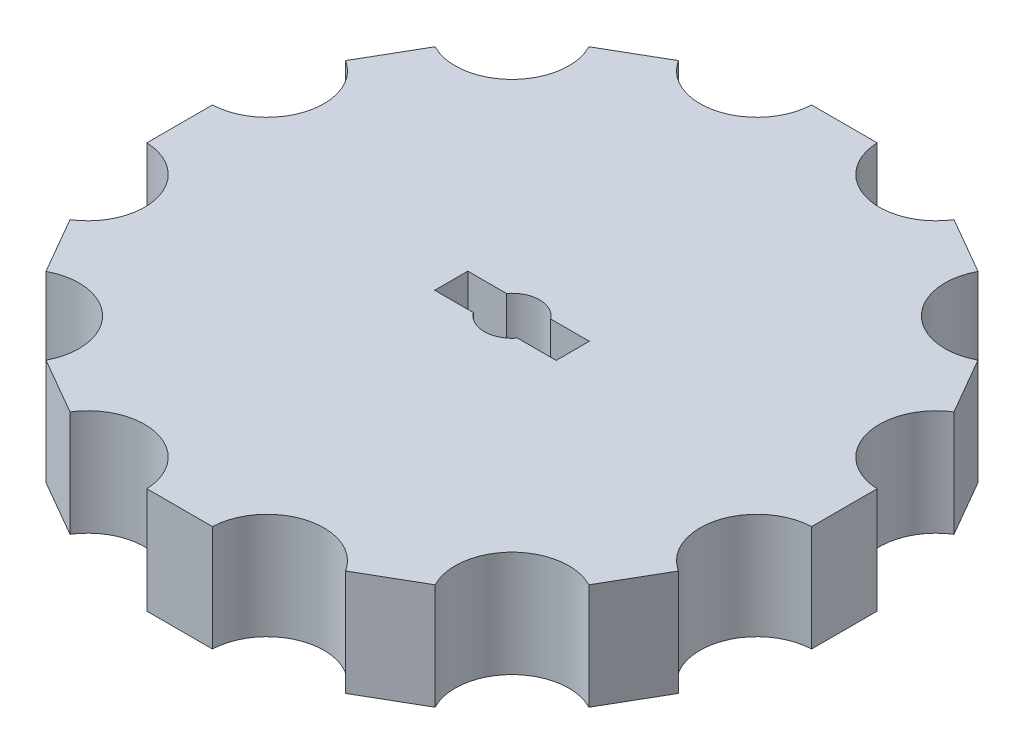
SolidWorks part; units mm, degrees
ref_plane "Front Plane" through (0, 0, 0) normal (0, 0, 1) x (1, 0, 0)
ref_plane "Top Plane" through (0, 0, 0) normal (0, 1, 0) x (1, 0, 0)
ref_plane "Right Plane" through (0, 0, 0) normal (1, 0, 0) x (0, 0, -1)
sketch "Sketch1" plane through (0, 0, 0) normal (0, 1, 0) x (1, 0, 0)
  line L0 (8.115, 30.2856) -> (3.165, 30.2856) construction
  line L1 (-8.115, -30.2856) -> (8.115, -30.2856)
  line L2 (8.115, -30.2856) -> (22.1706, -22.1706)
  line L3 (22.1706, -22.1706) -> (26.2281, -15.1428)
  line L4 (30.2856, -2.965) -> (30.2856, 0) construction
  line L5 (30.2856, 8.115) -> (27.7106, 12.575) construction
  line L6 (17.7106, 24.7456) -> (15.1428, 26.2281) construction
  line L7 (3.165, 30.2856) -> (-3.165, 30.2856) construction
  line L8 (-12.575, 27.7106) -> (-22.1706, 22.1706)
  line L9 (-22.1706, 22.1706) -> (-30.2856, 8.115)
  line L10 (-30.2856, 8.115) -> (-30.2856, -8.115)
  line L11 (-30.2856, -8.115) -> (-22.1706, -22.1706)
  line L12 (-22.1706, -22.1706) -> (-8.115, -30.2856)
  line L13 (12.4018, 27.8106) -> (8.115, 30.2856) construction
  line L14 (-8.115, 30.2856) -> (-12.4018, 27.8106) construction
  line L15 (-3.165, 30.2856) -> (-8.115, 30.2856) construction
  line L16 (2.9689, 30.0856) -> (-2.9689, 30.0856)
  line L17 (-12.4018, 27.8106) -> (-12.575, 27.7106) construction
  line L18 (17.6139, 24.5704) -> (12.4717, 27.5393)
  line L19 (27.5393, 12.4717) -> (24.5704, 17.6139)
  line L20 (30.0856, -2.9689) -> (30.0856, 2.9689)
  line L21 (24.4724, -17.7838) -> (27.5393, -12.4717)
  line L22 (12.3018, -27.6374) -> (17.6139, -24.5704)
  line L23 (-3.165, -30.0856) -> (2.9689, -30.0856)
  line L24 (-17.7838, -24.4724) -> (-12.4717, -27.5393)
  line L25 (-27.6374, -12.3018) -> (-24.5704, -17.6139)
  line L26 (-30.0856, 3.165) -> (-30.0856, -2.9689)
  line L27 (-24.4724, 17.7838) -> (-27.5393, 12.4717)
  line L28 (-12.4717, 27.5393) -> (-17.6139, 24.5704)
  line L29 (-12.3018, 27.6374) -> (-12.4717, 27.5393) construction
  line L30 (15.1428, 26.2281) -> (12.4018, 27.8106) construction
  line L31 (3.165, 30.0856) -> (2.9689, 30.0856) construction
  line L32 (3.165, 30.0856) -> (-2.9689, 30.0856) construction
  line L33 (22.1706, 22.1706) -> (17.7106, 24.7456) construction
  line L34 (17.7838, 24.4724) -> (17.6139, 24.5704) construction
  line L35 (26.2281, 15.1428) -> (22.1706, 22.1706) construction
  line L36 (27.6374, 12.3018) -> (27.5393, 12.4717) construction
  line L37 (27.7106, 12.575) -> (26.2281, 15.1428) construction
  line L38 (30.2856, 0) -> (30.2856, 8.115) construction
  line L39 (30.2856, -8.115) -> (30.2856, -2.965) construction
  line L40 (26.2281, -15.1428) -> (30.2856, -8.115) construction
  line L41 (30.0856, -3.165) -> (30.0856, -2.9689) construction
  circle A0 centre (0, 0) radius 30.2856 construction
  arc A1 (-12.4018, 27.8106) -> (-3.165, 30.2856) centre (-8.115, 30.2856) ccw construction
  arc A2 (3.165, 30.2856) -> (3.1678, 30.1195) centre (8.115, 30.2856) ccw construction
  arc A3 (-3.165, 30.2856) -> (-12.4018, 27.8106) centre (-8.115, 30.2856) ccw construction
  arc A4 (12.4018, 27.8106) -> (3.165, 30.2856) centre (8.115, 30.2856) ccw construction
  arc A5 (-12.4717, 27.5393) -> (-2.9689, 30.0856) centre (-8.115, 30.2856) ccw
  arc A6 (2.9689, 30.0856) -> (12.4717, 27.5393) centre (8.115, 30.2856) ccw
  arc A7 (17.6395, 24.6184) -> (24.5704, 17.6139) centre (22.1706, 22.1706) ccw
  arc A8 (27.5855, 12.5004) -> (30.0856, 2.9689) centre (30.2856, 8.115) ccw
  arc A9 (30.0856, -2.9689) -> (27.5393, -12.4717) centre (30.2856, -8.115) ccw
  arc A10 (24.7456, -17.7106) -> (17.6139, -24.5704) centre (22.1706, -22.1706) ccw
  arc A11 (12.575, -27.7106) -> (2.9689, -30.0856) centre (8.115, -30.2856) ccw
  arc A12 (-2.965, -30.2856) -> (-12.4717, -27.5393) centre (-8.115, -30.2856) ccw
  arc A13 (-17.7106, -24.7456) -> (-24.5704, -17.6139) centre (-22.1706, -22.1706) ccw
  arc A14 (-27.7106, -12.575) -> (-30.0856, -2.9689) centre (-30.2856, -8.115) ccw
  arc A15 (-30.2856, 2.965) -> (-27.5393, 12.4717) centre (-30.2856, 8.115) ccw
  arc A16 (-24.7456, 17.7106) -> (-17.6139, 24.5704) centre (-22.1706, 22.1706) ccw
  arc A17 (-12.5004, 27.5855) -> (-12.4717, 27.5393) centre (-8.115, 30.2856) ccw construction
  arc A18 (-12.575, 27.7106) -> (-12.5004, 27.5855) centre (-8.115, 30.2856) ccw construction
  arc A19 (-12.575, 27.7106) -> (-2.9689, 30.0856) centre (-8.115, 30.2856) ccw construction
  arc A20 (2.965, 30.2856) -> (2.9671, 30.1399) centre (8.115, 30.2856) ccw construction
  arc A21 (2.9671, 30.1399) -> (2.9689, 30.0856) centre (8.115, 30.2856) ccw construction
  arc A22 (12.3163, 27.6681) -> (12.4018, 27.8106) centre (8.115, 30.2856) ccw construction
  arc A23 (3.1678, 30.1195) -> (12.3163, 27.6681) centre (8.115, 30.2856) ccw construction
  arc A24 (17.7106, 24.7456) -> (17.6395, 24.6184) centre (22.1706, 22.1706) ccw construction
  arc A25 (27.7106, 12.575) -> (27.5855, 12.5004) centre (30.2856, 8.115) ccw construction
  arc A26 (30.2856, -2.965) -> (30.1399, -2.9671) centre (30.2856, -8.115) ccw construction
  arc A27 (30.1399, -2.9671) -> (30.0856, -2.9689) centre (30.2856, -8.115) ccw construction
  point P69 (0, 0)
  dimension "D2" = 9.9
  dimension "D1" = 16.23
  dimension "D3" = 0.2
extrude "Boss-Extrude1" add sketch "Sketch1" along normal blind 9.6 contours A16 L27 A15 L26 A14 L25 A13 L24 A12 L23 A11 L22 A10 L21 A9 L20 A8 L19 A7 L18 A6 L16 A5 L28
sketch "Sketch2" plane through (0, 9.6, 0) normal (0, 1, 0) x (1, 0, 0)
  line L0 (-2, -1.5) -> (-5.5, -1.5)
  line L1 (-5.5, -1.5) -> (-5.5, 1.5)
  line L2 (-5.5, 1.5) -> (-2, 1.5)
  line L3 (0, 0) -> (-2.5, 0) construction
  line L4 (-2.5, 0) -> (-5.5, 0) construction
  line L5 (0, 2.5) -> (0, -2.5) construction
  line L6 (5.5, 1.5) -> (2, 1.5)
  line L7 (5.5, -1.5) -> (5.5, 1.5)
  line L8 (2, -1.5) -> (5.5, -1.5)
  arc A0 (-2, -1.5) -> (2, -1.5) centre (0, 0) ccw
  arc A1 (-2.5, 0) -> (-2, -1.5) centre (0, 0) ccw construction
  arc A2 (-2, 1.5) -> (-2.5, 0) centre (0, 0) ccw construction
  arc A3 (2, 1.5) -> (-2, 1.5) centre (0, 0) ccw
  arc A4 (2, -1.5) -> (2, 1.5) centre (0, 0) ccw construction
  point P11 (0, 0)
  dimension "D1" = 5
  dimension "D2" = 3
  dimension "D3" = 3
extrude "Cut-Extrude1" cut sketch "Sketch2" against normal through all
